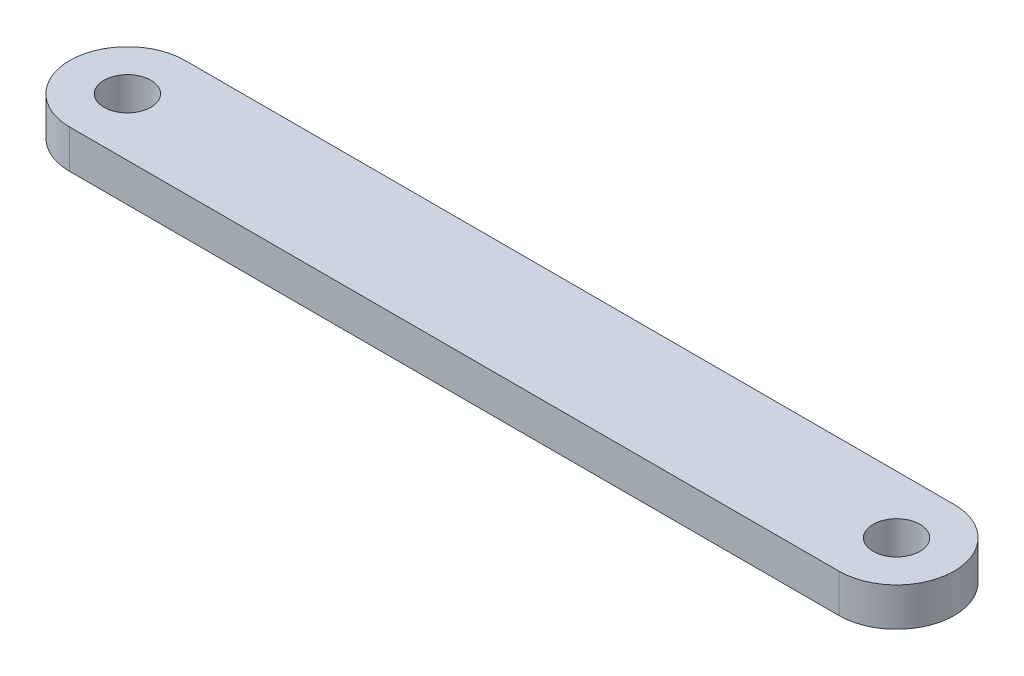
SolidWorks part; units mm, degrees
ref_plane "Front Plane" through (0, 0, 0) normal (0, 0, 1) x (1, 0, 0)
ref_plane "Top Plane" through (0, 0, 0) normal (0, 1, 0) x (1, 0, 0)
ref_plane "Right Plane" through (0, 0, 0) normal (1, 0, 0) x (0, 0, -1)
sketch "Sketch1" plane through (0, 0, 0) normal (0, 1, 0) x (1, 0, 0)
  line L0 (0, 0) -> (-50.8, 0) construction
  line L1 (0, -3.81) -> (-50.8, -3.81)
  line L2 (0, 3.81) -> (-50.8, 3.81)
  arc A0 (0, -3.81) -> (0, 3.81) centre (0, 0) ccw
  arc A1 (-50.8, 3.81) -> (-50.8, -3.81) centre (-50.8, 0) ccw
  circle A2 centre (-50.8, 0) radius 1.55
  circle A3 centre (0, 0) radius 1.55
  point P3 (-25.4, 0)
  dimension "D2" = 3.1
  dimension "D1" = 50.8
  dimension "D3" = 7.62
extrude "Boss-Extrude1" add sketch "Sketch1" along normal blind 2.54
